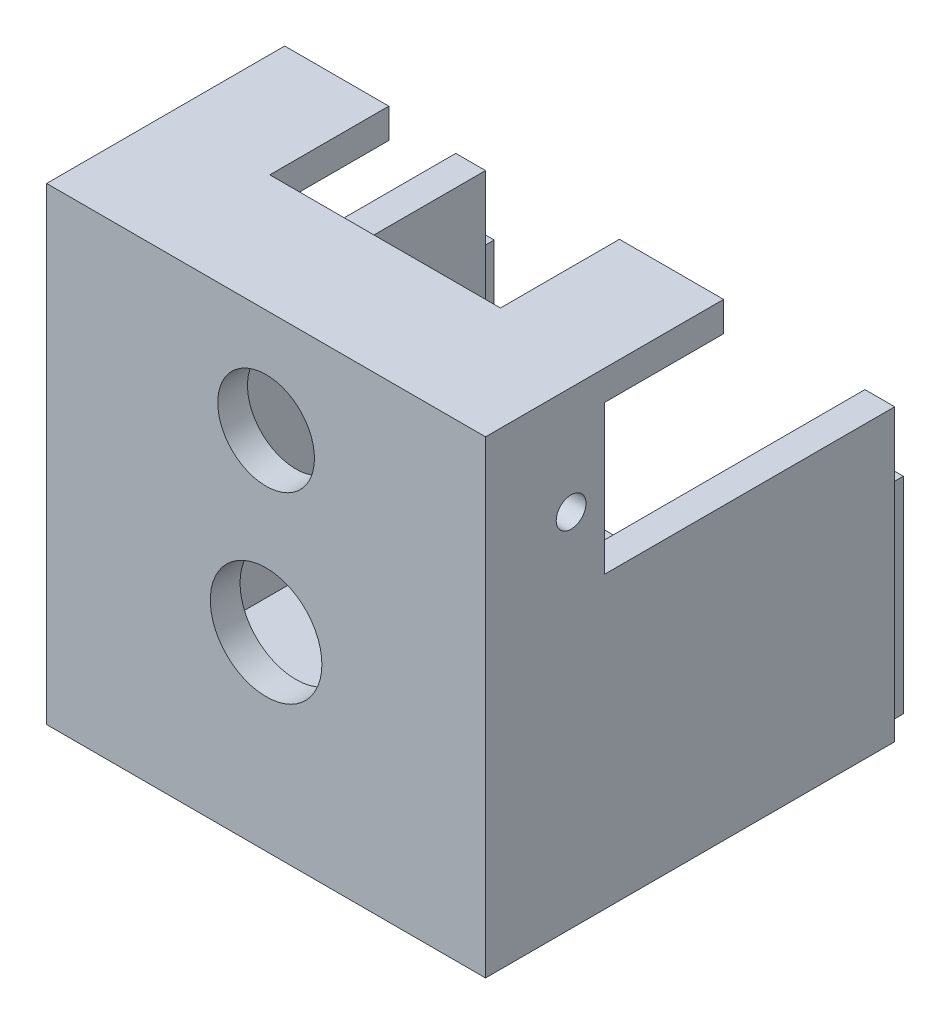
SolidWorks part; units mm, degrees
ref_plane "Płaszczyzna przednia" through (0, 0, 0) normal (0, 0, 1) x (1, 0, 0)
ref_plane "Płaszczyzna górna" through (0, 0, 0) normal (0, 1, 0) x (1, 0, 0)
ref_plane "Płaszczyzna prawa" through (0, 0, 0) normal (1, 0, 0) x (0, 0, -1)
sketch "Sketch1" plane through (0, 0, 0) normal (0, 0, 1) x (1, 0, 0)
  line L1 (-29.5, -10) -> (29.5, -10)
  line L2 (-29.5, -10) -> (-29.5, 10)
  line L3 (-29.5, 10) -> (29.5, 10)
  line L4 (29.5, -10) -> (29.5, 10)
  line L5 (-29.5, -10) -> (29.5, 10) construction
  line L6 (-29.5, 10) -> (29.5, -10) construction
  circle A0 centre (0, 0) radius 6.5
  point P0 (0, 0)
  dimension "D1" = 59
  dimension "D2" = 20
extrude "Boss-Extrude1" add sketch "Sketch1" along normal blind 4
sketch "Sketch2" plane through (0, 10, 0) normal (0, 1, 0) x (1, 0, 0)
  line L0 (-29.5, -4) -> (29.5, -4)
  line L1 (-29.5, -4) -> (-29.5, 12)
  line L2 (29.5, -4) -> (29.5, 12)
  line L3 (-29.5, 12) -> (29.5, 12)
  dimension "D1" = 16
extrude "Boss-Extrude2" add sketch "Sketch2" along normal blind 4
sketch "Sketch3" plane through (0, 0, -12) normal (0, 0, -1) x (-1, 0, 0)
  line L0 (-29.5, 14) -> (29.5, 14) construction
  line L1 (-29.5, 10) -> (-15.5, 10)
  line L2 (-29.5, 10) -> (-29.5, 14)
  line L3 (-29.5, 14) -> (-15.5, 14)
  line L4 (-15.5, 10) -> (-15.5, 14)
  line L5 (-29.5, 10) -> (29.5, 10) construction
  line L6 (29.5, 14) -> (15.5, 14)
  line L7 (29.5, 14) -> (29.5, 10)
  line L8 (29.5, 10) -> (15.5, 10)
  line L9 (15.5, 14) -> (15.5, 10)
  dimension "D1" = 14
  dimension "D2" = 14
extrude "Boss-Extrude3" add sketch "Sketch3" along normal blind 16
sketch "Sketch4" plane through (0, 0, 0) normal (0, 0, -1) x (-1, 0, 0)
  line L0 (15.5, 10) -> (29.5, 10) construction
  line L1 (29.5, -10) -> (25.5, -10)
  line L2 (29.5, -10) -> (29.5, 10)
  line L3 (29.5, 10) -> (25.5, 10)
  line L4 (25.5, -10) -> (25.5, 10)
  line L5 (-29.5, 10) -> (-15.5, 10) construction
  line L6 (-29.5, -10) -> (-25.5, -10)
  line L7 (-29.5, -10) -> (-29.5, 10)
  line L8 (-29.5, 10) -> (-25.5, 10)
  line L9 (-25.5, -10) -> (-25.5, 10)
  dimension "D1" = 4
  dimension "D2" = 4
  dimension "D3" = 20
extrude "Boss-Extrude4" add sketch "Sketch4" along normal blind 12
sketch "Sketch5" plane through (-29.5, 0, 0) normal (-1, 0, 0) x (0, 0, 1)
  line L0 (-12, -10) -> (-12, 10) construction
  line L1 (-28, 10) -> (-12, 10) construction
  line L2 (4, -10) -> (-12, -10) construction
  circle A0 centre (-7.5, -0.5) radius 2
  dimension "D1" = 4.5
  dimension "D2" = 10.5
  dimension "D3" = 9.5
extrude "Cut-Extrude1" cut sketch "Sketch5" against normal blind 80
sketch "Sketch8" plane through (0, -10, 0) normal (0, -1, 0) x (1, 0, 0)
  line L0 (25.5, -51) -> (29.5, -51)
  line L1 (-29.5, 4) -> (29.5, 4)
  line L2 (-29.5, 4) -> (-29.5, -51)
  line L3 (-29.5, -51) -> (-25.5, -51)
  line L4 (29.5, 4) -> (29.5, -51)
  line L5 (-25.5, 0) -> (25.5, 0)
  line L6 (-25.5, 0) -> (-25.5, -51)
  line L8 (25.5, 0) -> (25.5, -51)
  dimension "D1" = 55
extrude "Boss-Extrude7" add sketch "Sketch8" along normal blind 35
sketch "Sketch9" plane through (0, -45, 0) normal (0, -1, 0) x (1, 0, 0)
  line L1 (-29.5, 4) -> (29.5, 4)
  line L2 (-29.5, 4) -> (-29.5, -51)
  line L3 (-29.5, -51) -> (29.5, -51)
  line L4 (29.5, 4) -> (29.5, -51)
extrude "Boss-Extrude8" add sketch "Sketch9" along normal blind 4
sketch "Sketch10" plane through (0, 0, -51) normal (0, 0, -1) x (-1, 0, 0)
  line L1 (-26.8333, -47.6667) -> (28.1667, -47.6667)
  line L2 (29.5, -49) -> (28.1667, -49) construction
  line L3 (-26.8333, -47.6667) -> (-26.8333, -46.3333)
  line L4 (29.5, -49) -> (29.5, -47.6667) construction
  line L9 (-29.5, -49) -> (-28.1667, -49) construction
  line L10 (-29.5, -49) -> (-29.5, -47.6667) construction
  line L11 (-29.5, -47.6667) -> (-28.1667, -47.6667) construction
  line L12 (-28.1667, -49) -> (-28.1667, -47.6667) construction
  line L13 (-29.5, -10) -> (-28.1667, -10) construction
  line L14 (-29.5, -10) -> (-29.5, -20) construction
  line L15 (-29.5, -20) -> (-28.1667, -20) construction
  line L16 (-28.1667, -10) -> (-28.1667, -20) construction
  line L17 (29.5, -10) -> (28.1667, -10) construction
  line L18 (29.5, -10) -> (29.5, -20) construction
  line L19 (29.5, -20) -> (28.1667, -20) construction
  line L20 (28.1667, -10) -> (28.1667, -20) construction
  line L22 (28.1667, -49) -> (28.1667, -47.6667) construction
  line L23 (-28.1667, -20) -> (-26.8333, -20)
  line L24 (-28.1667, -20) -> (-28.1667, -47.6667)
  line L25 (-28.1667, -47.6667) -> (-26.8333, -47.6667)
  line L26 (-26.8333, -20) -> (-26.8333, -47.6667)
  line L27 (-26.8333, -46.3333) -> (28.1667, -46.3333)
  line L28 (28.1667, -47.6667) -> (28.1667, -46.3333)
  line L29 (28.1667, -46.3333) -> (26.8333, -46.3333)
  line L30 (28.1667, -46.3333) -> (28.1667, -20)
  line L31 (28.1667, -20) -> (26.8333, -20)
  line L32 (26.8333, -46.3333) -> (26.8333, -20)
  dimension "D2" = 1.3333
  dimension "D5" = 1.3333
  dimension "D6" = 10
  dimension "D7" = 10
  dimension "D8" = 1.3333
  dimension "D9" = 1.3333
  dimension "D10" = 1.3333
  dimension "D11" = 1.3333
extrude "Boss-Extrude9" add sketch "Sketch10" along normal blind 2.5 contours L26 L23 L24 L25 L3 | L1 L28 L27 L3 | L32 L27 L30 L31
sketch "Sketch11" plane through (0, 0, 4) normal (0, 0, 1) x (1, 0, 0)
  line L0 (0, 14) -> (0, -16) construction
  line L1 (-29.5, 14) -> (29.5, 14) construction
  line L2 (0, -16) -> (0, -23.5) construction
  circle A0 centre (0, -23.5) radius 7.5
  dimension "D1" = 30
  dimension "D2" = 7.5
extrude "Cut-Extrude2" cut sketch "Sketch11" against normal blind 5
